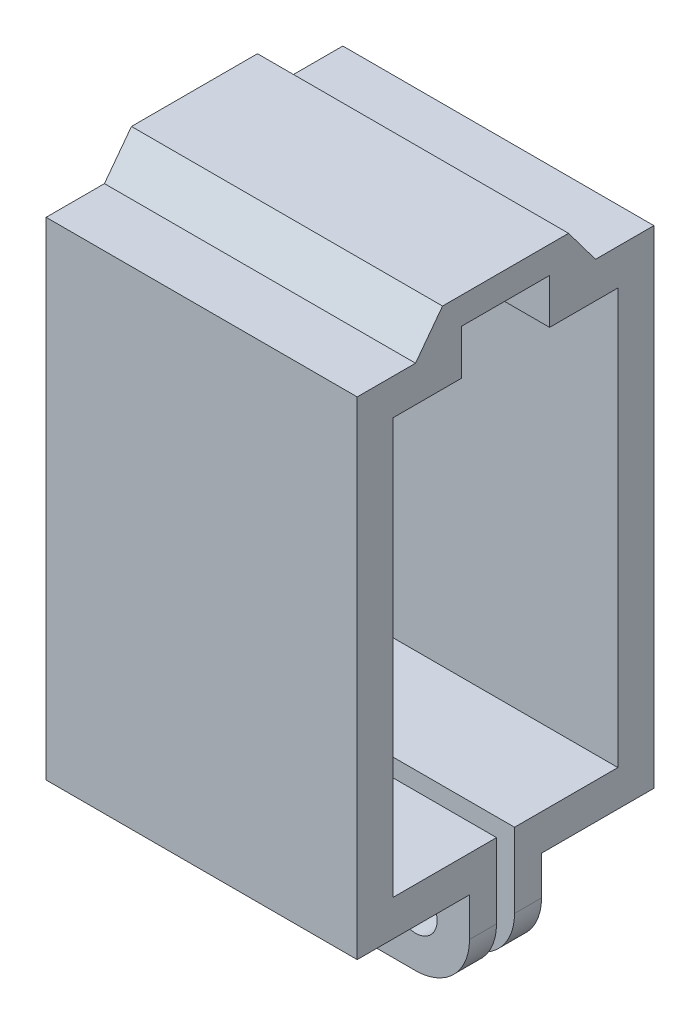
SolidWorks part; units mm, degrees
ref_plane "Front Plane" through (0, 0, 0) normal (0, 0, 1) x (1, 0, 0)
ref_plane "Top Plane" through (0, 0, 0) normal (0, 1, 0) x (1, 0, 0)
ref_plane "Right Plane" through (0, 0, 0) normal (1, 0, 0) x (0, 0, -1)
sketch "Sketch1" plane through (0, 0, 0) normal (1, 0, 0) x (0, 0, -1)
  line L0 (6.24, 6.24) -> (-6.24, 6.24)
  line L1 (-6.24, 6.24) -> (-6.24, -16.8311)
  line L2 (-6.24, -16.8311) -> (6.24, -16.8311)
  line L3 (6.24, -16.8311) -> (6.24, 6.24)
  line L4 (6.09, 6.09) -> (-6.09, 6.09)
  line L5 (-6.09, 6.09) -> (-6.09, -16.6811)
  line L6 (-6.09, -16.6811) -> (6.09, -16.6811)
  line L7 (6.09, -16.6811) -> (6.09, 6.09)
  line L8 (6.09, 6.09) -> (-6.09, 6.09) construction
  line L9 (-6.09, 6.09) -> (-6.09, -16.6811) construction
  line L10 (-6.09, -16.6811) -> (6.09, -16.6811) construction
  line L11 (6.09, -16.6811) -> (6.09, 6.09) construction
  line L12 (8.24, 8.24) -> (-8.24, 8.24)
  line L13 (-8.24, 8.24) -> (-8.24, -18.8311)
  line L14 (-8.24, -18.8311) -> (8.24, -18.8311)
  line L15 (8.24, -18.8311) -> (8.24, 8.24)
  dimension "D1" = 0
  dimension "D2" = 0.15
  dimension "D3" = 2
extrude "Boss-Extrude1" add sketch "Sketch1" along normal offset from surface (17.2796 mm away) 0.5
sketch "Sketch2" plane through (17.2796, 0, 0) normal (1, 0, 0) x (0, 0, -1)
  line L0 (8.24, 8.24) -> (-8.24, 8.24) construction
  line L1 (-5, 8.24) -> (5, 8.24)
  line L3 (-3.5, 10.24) -> (3.5, 10.24)
  line L5 (-5, 8.24) -> (-3.5, 10.24)
  line L6 (5, 8.24) -> (3.5, 10.24)
  line L7 (0, 10.24) -> (0, 8.24) construction
  point P6 (0, 8.24)
  dimension "D1" = 2
  dimension "D2" = 7
  dimension "D3" = 10
extrude "Boss-Extrude2" add sketch "Sketch2" against normal up to surface (17.2796 mm away) up to face at (0, -5.2956, 0)
sketch "Sketch3" plane through (17.2796, 0, 0) normal (1, 0, 0) x (0, 0, -1)
  line L0 (-1.4478, 7.74) -> (1.4478, 7.74) construction
  line L1 (-2.4478, 5.09) -> (2.4478, 5.09)
  line L2 (2.4478, 5.09) -> (2.4478, 8.74)
  line L3 (-2.4478, 8.74) -> (2.4478, 8.74)
  line L4 (-1.4478, 6.09) -> (1.4478, 6.09)
  line L5 (1.4478, 6.09) -> (1.4478, 12.186)
  line L6 (1.4478, 12.186) -> (-1.4478, 12.186)
  line L7 (-1.4478, 12.186) -> (-1.4478, 6.09)
  line L8 (-1.4478, 6.09) -> (1.4478, 6.09) construction
  line L9 (1.4478, 6.09) -> (1.4478, 7.74) construction
  line L11 (-1.4478, 7.74) -> (-1.4478, 6.09) construction
  line L12 (-2.4478, 8.74) -> (-2.4478, 5.09)
  line L13 (3.5, 10.24) -> (-3.5, 10.24) construction
  dimension "D2" = 1
  dimension "D3" = 1.5
  dimension "D1" = 0
extrude "Cut-Extrude1" cut sketch "Sketch3" against normal through all
sketch "Sketch4" plane through (17.2796, 0, 0) normal (1, 0, 0) x (0, 0, -1)
  line L0 (-8.24, -18.8311) -> (8.24, -18.8311) construction
  line L1 (-2, -18.8311) -> (2, -18.8311)
  line L2 (-2, -18.8311) -> (-2, -23.9811)
  line L3 (-2, -23.9811) -> (2, -23.9811)
  line L4 (2, -18.8311) -> (2, -23.9811)
  point P6 (0, -18.8311)
  dimension "D1" = 5.15
  dimension "D2" = 4
extrude "Boss-Extrude3" add sketch "Sketch4" against normal up to surface (17.2796 mm away) up to face at (0, 1.9722, 0)
sketch "Sketch5" plane through (17.2796, 0, 0) normal (1, 0, 0) x (0, 0, -1)
  line L0 (-6.24, -16.8311) -> (6.24, -16.8311) construction
  line L1 (-0.5, -16.8311) -> (0.5, -16.8311)
  line L2 (-0.5, -16.8311) -> (-0.5, -23.9811)
  line L3 (-0.5, -23.9811) -> (0.5, -23.9811)
  line L4 (0.5, -16.8311) -> (0.5, -23.9811)
  line L5 (-2, -23.9811) -> (2, -23.9811) construction
  point P8 (0, -16.8311)
  dimension "D1" = 1
fillet "Fillet1" radius 3 2 edges at (0, -23.9811, 0) (17.2796, -23.9811, 0)
extrude "Cut-Extrude3" cut sketch "Sketch5" against normal through all
hole_wizard "M2 Clearance Hole1" positions "Sketch6" profile "Sketch7" hole size "M2" standard "ANSI Metric" end condition through all
sketch "Sketch6" plane through (0, 0, -2) normal (0, 0, -1) x (-1, 0, 0)
  point P0 (-14.2796, -20.9811)
  point P3 (-3, -20.9811)
sketch "Sketch7" plane through (14.2796, -20.9811, -2) normal (1, 0, 0) x (0, 1, 0)
  line L0 (0, 0) -> (0, 10.24)
  line L1 (0, 10.24) -> (1.2, 10.24)
  line L2 (1.2, 10.24) -> (1.2, 0)
  line L5 (1.2, 0) -> (0, 0)
  line L11 (0, -6.35) -> (0, 107.95) construction
  dimension "Thru Hole Dia." = 2.4
  dimension "Thru Hole Depth" = 10.24
